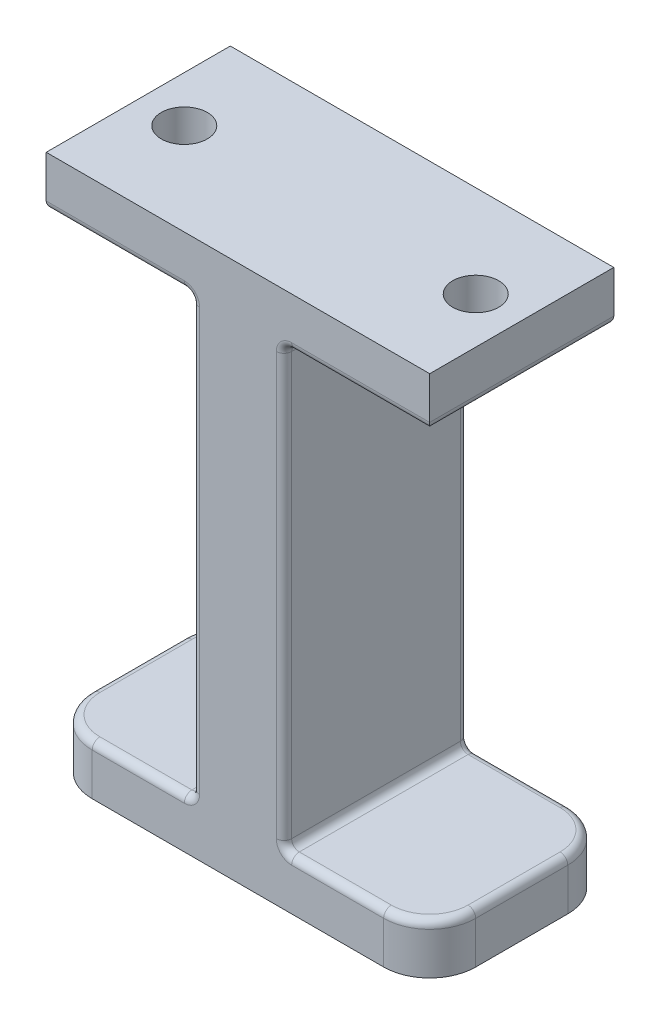
SolidWorks part; units mm, degrees
material "AISI 1020"
ref_plane "Front Plane" through (0, 0, 0) normal (0, 0, 1) x (1, 0, 0)
ref_plane "Top Plane" through (0, 0, 0) normal (0, 1, 0) x (1, 0, 0)
ref_plane "Right Plane" through (0, 0, 0) normal (1, 0, 0) x (0, 0, -1)
sketch "Sketch1" plane through (0, 0, 0) normal (0, 0, 1) x (1, 0, 0)
  line L0 (0, 0) -> (-12.5, 0)
  line L1 (-12.5, 0) -> (-12.5, 3.25)
  line L2 (-12.5, 3.25) -> (-3, 3.25)
  line L3 (-3, 3.25) -> (-3, 31.75)
  line L4 (-3, 31.75) -> (-12.5, 31.75)
  line L5 (-12.5, 31.75) -> (-12.5, 35)
  line L6 (-12.5, 35) -> (12.5, 35)
  line L7 (12.5, 35) -> (12.5, 31.75)
  line L8 (12.5, 31.75) -> (3, 31.75)
  line L9 (3, 31.75) -> (3, 3.25)
  line L10 (3, 3.25) -> (12.5, 3.25)
  line L11 (12.5, 3.25) -> (12.5, 0)
  line L12 (12.5, 0) -> (0, 0)
  point P15 (0, 35)
  point P16 (3, 17.5)
  dimension "D1" = 6
  dimension "D2" = 9.5
  dimension "D3" = 35
  dimension "D4" = 28.5
  dimension "D5" = 17.5
extrude "Boss-Extrude1" add sketch "Sketch1" along normal mid plane 12
fillet "Fillet1" radius 3 4 edges at (-12.5, 1.625, -6) (12.5, 1.625, -6) (-12.5, 1.625, 6) (12.5, 1.625, 6)
sketch "Sketch2" plane through (0, 35, 0) normal (0, 1, 0) x (1, 0, 0)
  line L0 (-12.5, -6) -> (-12.5, 6) construction
  line L1 (12.5, -6) -> (12.5, 6) construction
  circle A0 centre (-9.5, 0) radius 1.5
  circle A1 centre (9.5, 0) radius 1.5
  dimension "D1" = 3
  dimension "D2" = 3
  dimension "D3" = 3
extrude "Cut-Extrude1" cut sketch "Sketch2" against normal up to next
fillet "Fillet2" radius 0.5 24 edges at (-12.5, 3.25, 0) (12.5, 3.25, 0) (-11.6213, 3.25, 5.1213) (-11.6213, 3.25, -5.1213) (11.6213, 3.25, 5.1213) (11.6213, 3.25, -5.1213) (-7.75, 31.75, 6) (-7.75, 31.75, -6) (-6.25, 3.25, 6) (-6.25, 3.25, -6) (6.25, 3.25, 6) (6.25, 3.25, -6) (7.75, 31.75, 6) (7.75, 31.75, -6) (-3, 31.75, 0) (-3, 17.5, 6) (-3, 3.25, 0) (-3, 17.5, -6) (3, 3.25, 0) (3, 17.5, 6) (3, 31.75, 0) (3, 17.5, -6) (12.5, 31.75, 0) (-12.5, 31.75, 0)
